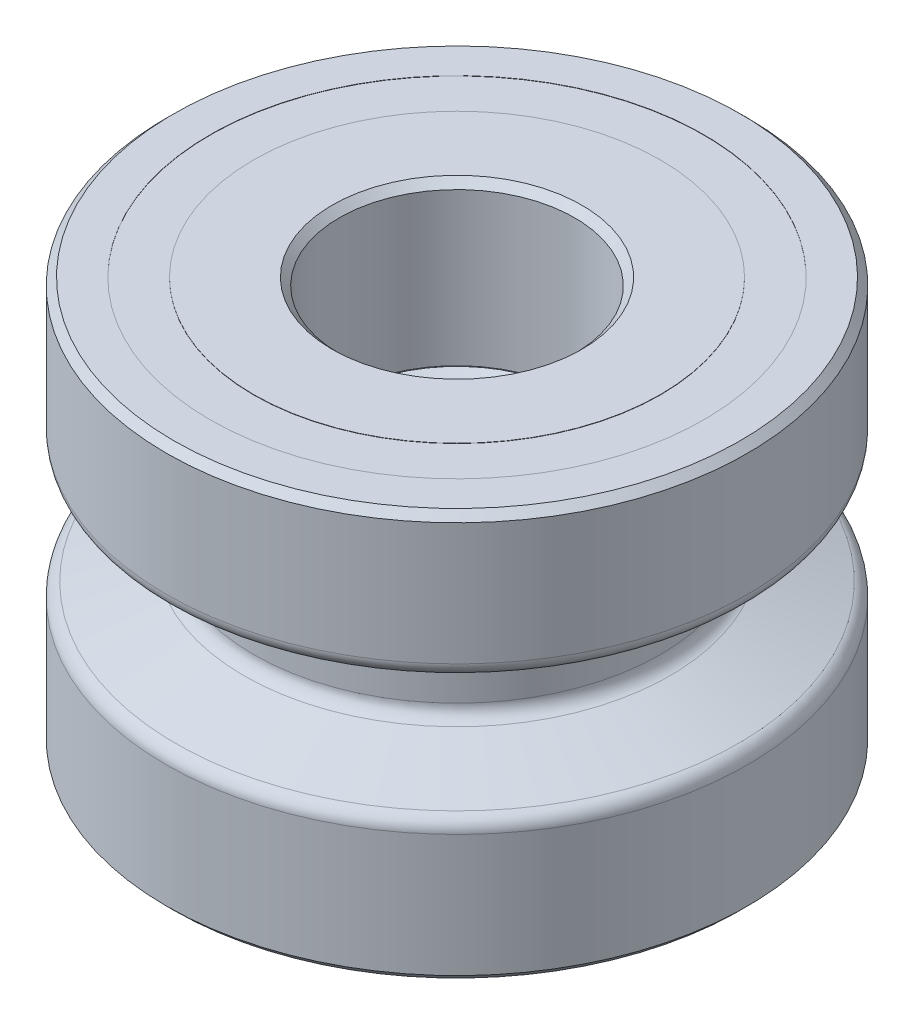
SolidWorks part; units mm, degrees
ref_plane "Front Plane" through (0, 0, 0) normal (0, 0, 1) x (1, 0, 0)
ref_plane "Top Plane" through (0, 0, 0) normal (0, 1, 0) x (1, 0, 0)
ref_plane "Right Plane" through (0, 0, 0) normal (1, 0, 0) x (0, 0, -1)
sketch "Sketch1" plane through (0, 0, 0) normal (0, 1, 0) x (1, 0, 0)
  circle A0 centre (0, 0) radius 10
  dimension "D1" = 20
extrude "Boss-Extrude1" add sketch "Sketch1" along normal mid plane 14
sketch "Sketch2" plane through (0, -7, 0) normal (0, -1, 0) x (1, 0, 0)
  circle A1 centre (0, 0) radius 3.5
  dimension "D1" = 7
extrude "Cut-Extrude1" cut sketch "Sketch2" against normal up to next
ref_axis "Axis1" through (0, 7, 0) along (0, -1, 0)
sketch "Sketch10" plane through (0, 0, 0) normal (0, 0, 1) x (1, 0, 0)
  line L0 (-4.2808, 0) -> (5.2603, 0) construction
  line L1 (10, 2.1919) -> (7, 1.1)
  line L2 (10, -7) -> (10, 7) construction
  line L4 (10, -2.1919) -> (7, -1.1)
  line L5 (10, 2.1919) -> (10, -2.1919)
  line L6 (7, 1.1) -> (7, -1.1)
  line L7 (7, 1.1) -> (10, 1.1) construction
  dimension "D1" = 3
  dimension "D2" = 2.2
  dimension "D3" = 20
revolve "Cut-Revolve1" cut sketch "Sketch10" angle 360 about axis through (0, 7, 0) along (0, -1, 0)
fillet "Fillet4" radius 0.5 4 edges at (0, -1.1, 7) (0, 1.1, 7) (0, 2.1919, 10) (0, -2.1919, 10)
sketch "Sketch11" plane through (0, -7, 0) normal (0, -1, 0) x (1, 0, 0)
  circle A0 centre (0, 0) radius 4.05
  dimension "D1" = 8.1
extrude "Cut-Extrude2" cut sketch "Sketch11" against normal blind 2.5
sketch "Sketch12" plane through (0, 7, 0) normal (0, 1, 0) x (1, 0, 0)
  circle A0 centre (0, 0) radius 4.05 construction
  circle A1 centre (0, 0) radius 4.05
extrude "Cut-Extrude3" cut sketch "Sketch12" against normal blind 5.5
sketch "Sketch13" plane through (0, 7, 0) normal (0, 1, 0) x (1, 0, 0)
  circle A1 centre (0, 0) radius 7
  circle A2 centre (0, 0) radius 8.5
  circle A3 centre (0, 0) radius 8.5
  dimension "D1" = 1.5
  dimension "D2" = 1.5
extrude "Cut-Extrude4" cut sketch "Sketch13" against normal blind 0.01
chamfer "Chamfer1" distance 0.25 angle 45 4 edges at (0, -7, 10) (0, -7, -4.05) (0, 7, 4.05) (0, 7, 10)
chamfer "Chamfer2" distance 0.3 angle 60 1 edges at (0, 1.5, 3.5)
